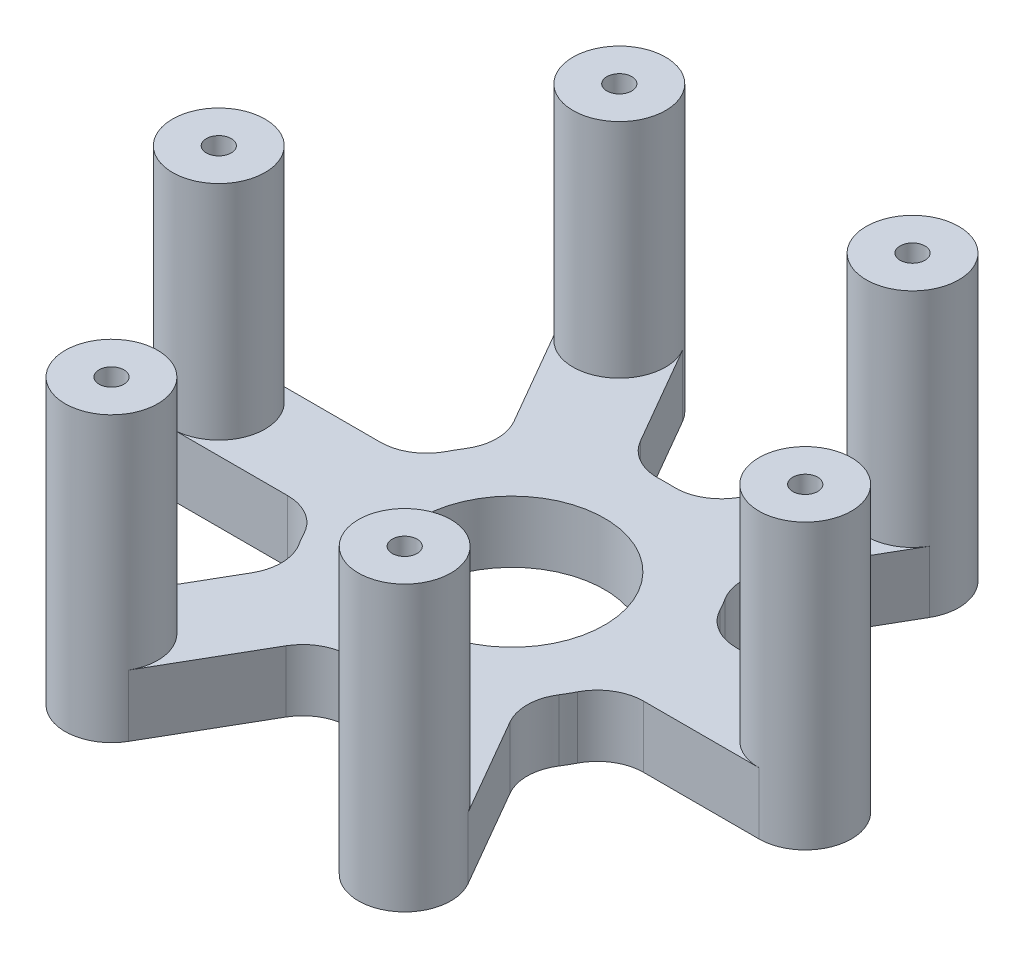
SolidWorks part; units mm, degrees
ref_plane "Front Plane" through (0, 0, 0) normal (0, 0, 1) x (1, 0, 0)
ref_plane "Top Plane" through (0, 0, 0) normal (0, 1, 0) x (1, 0, 0)
ref_plane "Right Plane" through (0, 0, 0) normal (1, 0, 0) x (0, 0, -1)
sketch "Sketch1" plane through (0, 0, 0) normal (0, 1, 0) x (1, 0, 0)
  line L0 (0, 15) -> (0, 25) construction
  circle A0 centre (0, 0) radius 25
  circle A1 centre (0, 0) radius 15
  dimension "D1" = 50
  dimension "D2" = 10
extrude "Boss-Extrude1" add sketch "Sketch1" along normal mid plane 10
sketch "Sketch2" plane through (0, -5, 0) normal (0, -1, 0) x (1, 0, 0)
  line L0 (25, 0) -> (55, 0) construction
  line L1 (54.4862, 7.5) -> (-23.8485, 7.5)
  line L2 (54.4862, -7.5) -> (-23.8485, -7.5)
  circle A0 centre (0, 0) radius 55
  circle A2 centre (0, 0) radius 25
  circle A3 centre (0, 0) radius 25 construction
  arc A4 (47.5, -7.5) -> (47.5, 7.5) centre (47.5, 0) ccw
  circle M4 centre (0, 0) radius 25
  dimension "D1" = 110
  dimension "D2" = 15
extrude "Boss-Extrude2" add sketch "Sketch2" against normal blind 10 contours A2 L0 A0 L1 | L0 L2 A0 M4
sketch "Sketch3" plane through (0, 5, 0) normal (0, 1, 0) x (1, 0, 0)
  circle A0 centre (0, 0) radius 47.5 construction
  point P3 (47.5, 0)
  dimension "D1" = 95
sketch "Sketch8" plane through (0, 5, 0) normal (0, 1, 0) x (1, 0, 0)
  circle A0 centre (47.5, 0) radius 7.5
  arc A1 (47.5, -7.5) -> (47.5, 7.5) centre (47.5, 0) ccw construction
extrude "Boss-Extrude4" add sketch "Sketch8" along normal blind 36
hole_wizard "Tap Drill for #10-32 Tap1" positions "Sketch9" profile "Sketch10" hole size "#10-32" standard "ANSI Inch" end condition up to next
sketch "Sketch9" plane through (0, -5, 0) normal (0, -1, 0) x (-1, 0, 0)
  point P0 (-47.5, 0)
sketch "Sketch10" plane through (47.5, -5, 0) normal (1, 0, 0) x (0, 0, -1)
  line L0 (0, 0) -> (0, 46)
  line L1 (0, 46) -> (2.0193, 46)
  line L2 (2.0193, 46) -> (2.0193, 0)
  line L5 (2.0193, 0) -> (0, 0)
  line L11 (0, -6.35) -> (0, 107.95) construction
  dimension "Thru Hole Dia." = 4.0386
  dimension "Thru Hole Depth" = 46
pattern_circular "CirPattern2" count 6 over 360 about axis through (0, 0, 0) along (0, 1, 0) of "Boss-Extrude1", "Tap Drill for #10-32 Tap1", "Boss-Extrude2", "Boss-Extrude4"
fillet "Fillet1" radius 7.5 12 edges at (23.8485, 0, -7.5) (23.8485, 0, 7.5) (-5.429, 0, -24.4034) (5.429, 0, -24.4034) (-23.8485, 0, -7.5) (-18.4194, 0, -16.9034) (-23.8485, 0, 7.5) (-18.4194, 0, 16.9034) (-5.429, 0, 24.4034) (5.429, 0, 24.4034) (18.4194, 0, 16.9034) (18.4194, 0, -16.9034)
equation "\"GEARDIST\"=26.62"
